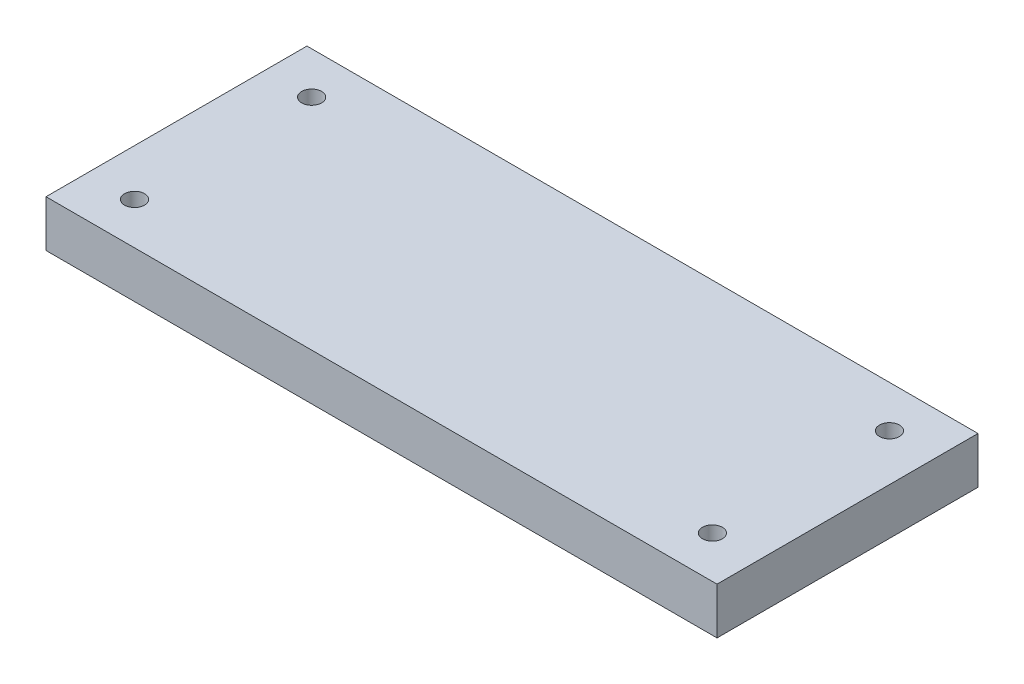
SolidWorks part; units mm, degrees
material "Low Carbon Steel"
ref_plane "Front Plane" through (0, 0, 0) normal (0, 0, 1) x (1, 0, 0)
ref_plane "Top Plane" through (0, 0, 0) normal (0, 1, 0) x (1, 0, 0)
ref_plane "Right Plane" through (0, 0, 0) normal (1, 0, 0) x (0, 0, -1)
sketch "Sketch1" plane through (0, 0, 0) normal (0, 1, 0) x (1, 0, 0)
  line L1 (-114.3, 44.45) -> (114.3, 44.45)
  line L2 (-114.3, 44.45) -> (-114.3, -44.45)
  line L3 (-114.3, -44.45) -> (114.3, -44.45)
  line L4 (114.3, 44.45) -> (114.3, -44.45)
  line L5 (-114.3, 44.45) -> (114.3, -44.45) construction
  line L6 (-114.3, -44.45) -> (114.3, 44.45) construction
  point P0 (0, 0)
  dimension "D1" = 88.9
  dimension "D2" = 228.6
extrude "Boss-Extrude1" add sketch "Sketch1" along normal blind 15.875
hole_wizard "M8x1.25 Tapped Hole1" positions "Sketch4" profile "Sketch3" tap size "M8x1.25" standard "ANSI Metric"
sketch "Sketch4" plane through (0, 15.875, 0) normal (0, 1, 0) x (1, 0, 0)
  line L0 (-98.425, -30.1625) -> (98.425, 30.1625) construction
  point P0 (-98.425, -30.1625)
  point P3 (-98.425, 30.1625)
  point P6 (98.425, 30.1625)
  point P9 (98.425, -30.1625)
  dimension "D1" = 196.85
  dimension "D2" = 60.325
sketch "Sketch3" plane through (-98.425, 15.875, 30.1625) normal (1, 0, 0) x (0, 0, 1)
  line L0 (0, 0) -> (0, 21.8041)
  line L1 (0, 21.8041) -> (3.4, 19.7612)
  line L2 (3.4, 19.7612) -> (3.4, 0)
  line L5 (3.4, 0) -> (0, 0)
  line L10 (0, 21.8041) -> (-3.4, 19.7612) construction
  line L11 (0, -6.35) -> (0, 107.95) construction
  dimension "Tap Drill Dia." = 6.8
  dimension "Tap Drill Depth" = 19.7612
  dimension "Drill Angle" = 118
cosmetic thread "Hole Thread1" parameters "D1"=15.875, "D2"=8
cosmetic thread "Hole Thread2" parameters "D1"=15.875, "D2"=8
cosmetic thread "Hole Thread3" parameters "D1"=15.875, "D2"=8
cosmetic thread "Hole Thread4" parameters "D1"=15.875, "D2"=8
other "Freeze***"
